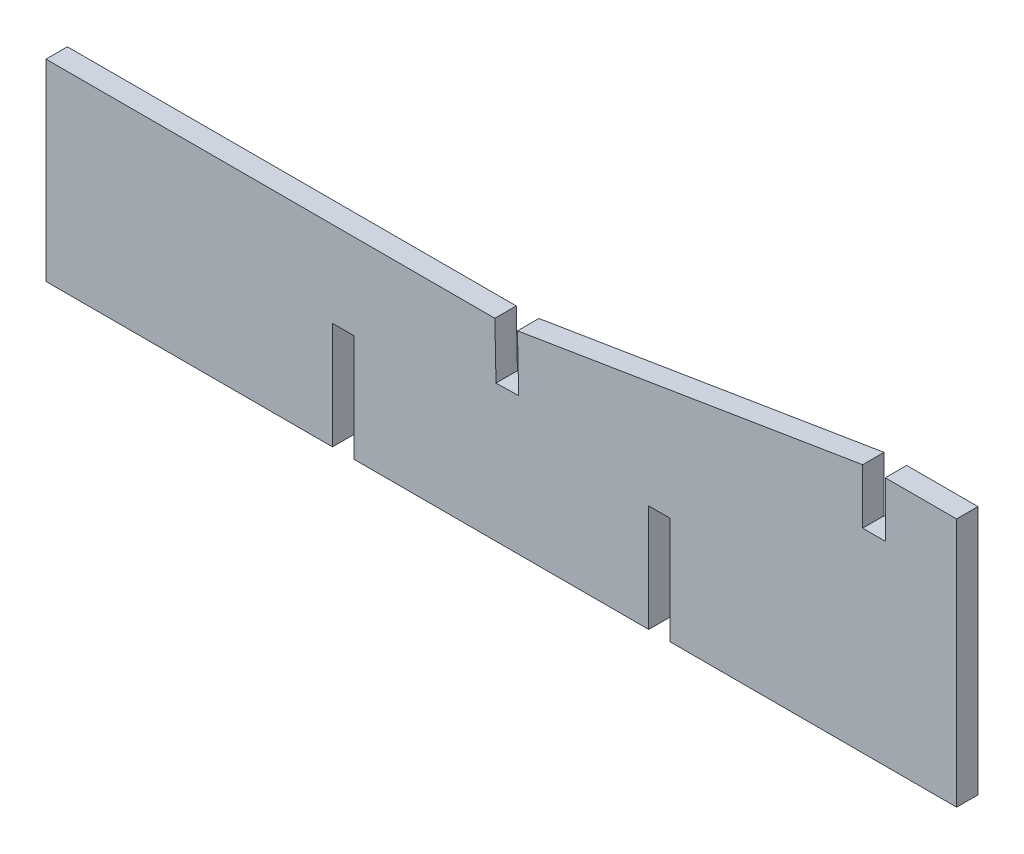
SolidWorks part; units mm, degrees
ref_plane "Front Plane" through (0, 0, 0) normal (0, 0, 1) x (1, 0, 0)
ref_plane "Top Plane" through (0, 0, 0) normal (0, 1, 0) x (1, 0, 0)
ref_plane "Right Plane" through (0, 0, 0) normal (1, 0, 0) x (0, 0, -1)
ref_plane "Plane1" through (0, 0, -573) normal (0, 0, 1) x (1, 0, 0)
sketch "Sketch1" plane through (0, 0, -573) normal (0, 0, 1) x (1, 0, 0)
  line L0 (374.396, 43.7428) -> (374.396, 51.451)
  line L1 (371.221, 43.7428) -> (371.221, 51.451)
  line L2 (371.221, 43.7428) -> (374.396, 43.7428)
  line L3 (374.396, 51.451) -> (371.221, 51.451)
  line L5 (371.221, 43.7428) -> (374.396, 43.7428)
  line L6 (371.221, 43.7428) -> (371.221, 51.451)
  line L7 (374.396, 43.7428) -> (374.396, 51.451)
  line L8 (322.8174, 43.5088) -> (322.9789, 35.7135)
  line L9 (319.643, 43.4436) -> (319.8046, 35.6483)
  line L10 (319.8046, 35.6483) -> (322.9789, 35.7135)
  line L11 (322.8174, 43.5088) -> (319.643, 43.4436)
  line L13 (319.8046, 35.6483) -> (322.9789, 35.7135)
  line L14 (319.643, 43.4436) -> (319.8046, 35.6483)
  line L15 (322.8174, 43.5088) -> (322.9789, 35.7135)
  line L16 (371.221, 51.451) -> (322.8174, 43.5088)
  line L17 (319.643, 43.4436) -> (256.7, 43.4436)
  line L18 (256.7, 43.4436) -> (256.7, 16.4388)
  line L19 (256.7, 16.4388) -> (296.875, 16.4388)
  line L20 (384.396, 16.4388) -> (384.396, 51.451)
  line L21 (384.396, 51.451) -> (374.396, 51.451)
  line L22 (266.7, 66.3394) -> (266.7, 36.5327) construction
  line L23 (269.875, 36.5327) -> (269.875, 66.3394) construction
  line L24 (371.221, 62.6017) -> (371.221, 32.0376) construction
  line L25 (299.875, 16.4388) -> (341.221, 16.4388)
  line L26 (344.221, 16.4388) -> (384.396, 16.4388)
  line L30 (296.875, 16.4388) -> (296.875, 31.4436)
  line L31 (296.875, 31.4436) -> (299.875, 31.4436)
  line L32 (299.875, 31.4436) -> (299.875, 16.4388)
  line L33 (341.221, 16.4388) -> (341.221, 31.4436)
  line L34 (341.221, 31.4436) -> (344.221, 31.4436)
  line L35 (344.221, 31.4436) -> (344.221, 16.4388)
  dimension "D1" = 10
  dimension "D2" = 10
  dimension "D3" = 3
  dimension "D4" = 3
  dimension "D5" = 30
  dimension "D6" = 30
  dimension "D7" = 12
extrude "Boss-Extrude1" add sketch "Sketch1" along normal blind 3
